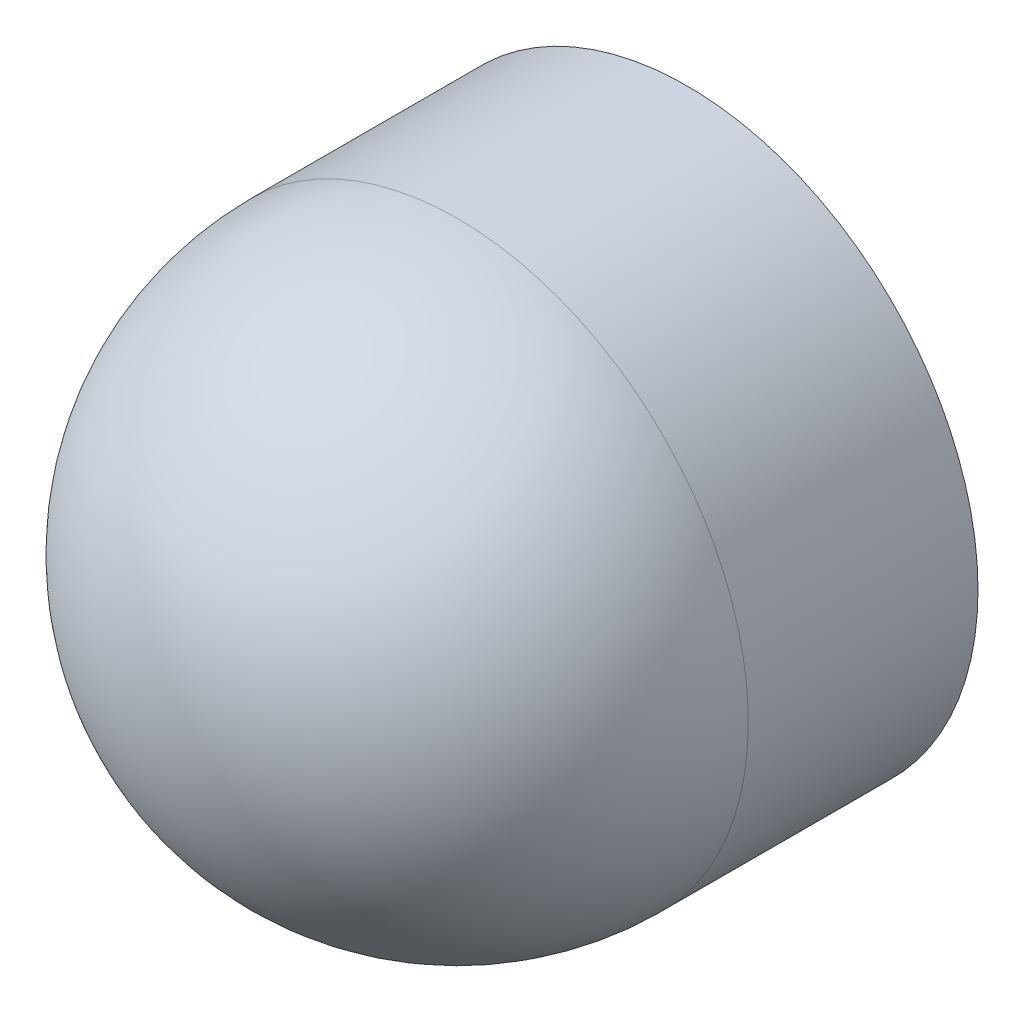
SolidWorks part; units mm, degrees
material "ABS"
ref_plane "Front Plane" through (0, 0, 0) normal (1, 0, 0) x (0, 1, 0)
ref_plane "Top Plane" through (0, 0, 0) normal (0, 0, 1) x (0, 1, 0)
ref_plane "Right Plane" through (0, 0, 0) normal (0, 1, 0) x (-1, 0, 0)
sketch "Sketch1" plane through (0, 0, 0) normal (1, 0, 0) x (0, 1, 0)
  line L0 (0, 7.62) -> (0, 17.272)
  line L1 (0, 0) -> (9.652, 0)
  line L2 (0, 0) -> (0, 7.62)
  line L4 (9.652, 0) -> (9.652, 7.62)
  arc A0 (9.652, 7.62) -> (0, 17.272) centre (0, 7.62) ccw
  dimension "D1" = 7.62
  dimension "D2" = 9.652
revolve "Revolve1" add sketch "Sketch1" angle 360 about L0
